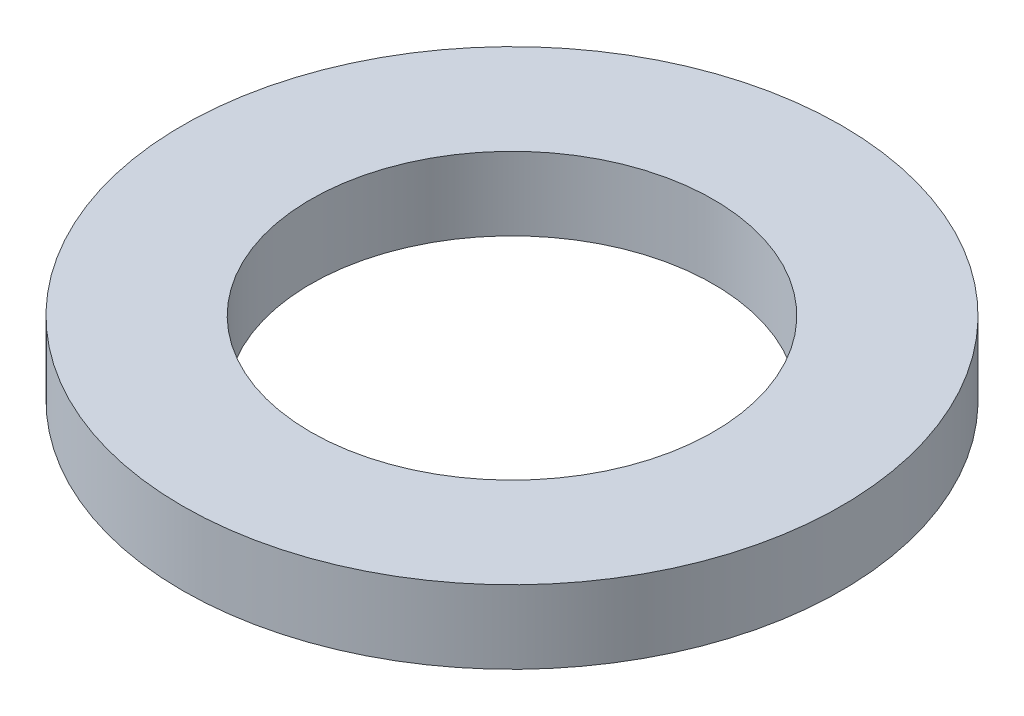
SolidWorks part; units mm, degrees
ref_plane "前视基准面" through (0, 0, 0) normal (0, 0, 1) x (1, 0, 0)
ref_plane "上视基准面" through (0, 0, 0) normal (0, 1, 0) x (1, 0, 0)
ref_plane "右视基准面" through (0, 0, 0) normal (1, 0, 0) x (0, 0, -1)
sketch "草图1" plane through (0, 0, 0) normal (0, 1, 0) x (1, 0, 0)
  circle A0 centre (0, 0) radius 4.5
  circle A1 centre (0, 0) radius 2.75
  dimension "D1" = 9
  dimension "D2" = 5.5
extrude "凸台-拉伸1" add sketch "草图1" along normal blind 1
